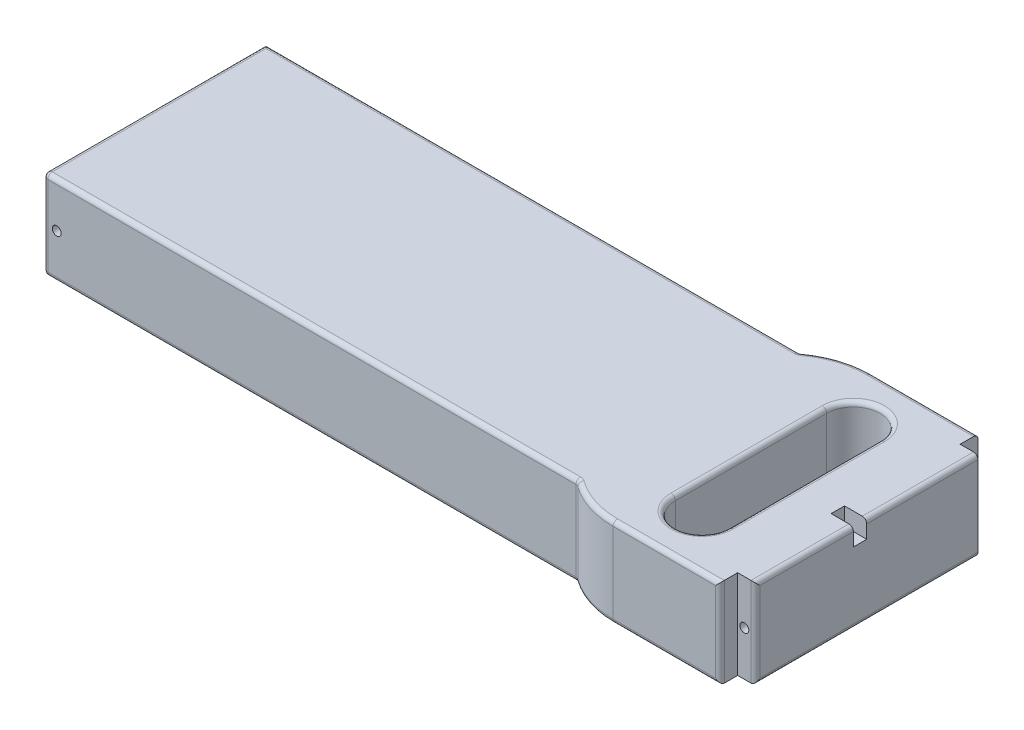
SolidWorks part; units mm, degrees
ref_plane "Alzado" through (0, 0, 0) normal (0, 0, 1) x (1, 0, 0)
ref_plane "Planta" through (0, 0, 0) normal (0, 1, 0) x (1, 0, 0)
ref_plane "Vista lateral" through (0, 0, 0) normal (1, 0, 0) x (0, 0, -1)
sketch "Croquis1" plane through (0, 0, 0) normal (0, 1, 0) x (1, 0, 0)
  line L0 (0, 0) -> (0, 1.3281)
  line L2 (8, 1.3281) -> (8, -1.1719)
  line L4 (0, -1.1719) -> (0, 0)
  line L5 (6, 1.3281) -> (0, 1.3281)
  line L10 (0, -1.1719) -> (6, -1.1719)
  line L11 (7.8, -1.3719) -> (7.8, -1.1719)
  line L12 (7.8, -1.1719) -> (8, -1.1719)
  line L13 (6.6, -1.3719) -> (7.8, -1.3719)
  line L14 (7.8, 1.5281) -> (7.8, 1.3281)
  line L15 (7.8, 1.3281) -> (8, 1.3281)
  line L16 (6.6, 1.5281) -> (7.8, 1.5281)
  arc A0 (6, 1.3281) -> (6.6, 1.5281) centre (6.6, 0.5281) cw
  arc A1 (6, -1.1719) -> (6.6, -1.3719) centre (6.6, -0.3719) ccw
  point P3 (6, 1.3281)
  point P11 (6, -1.1719)
  dimension "D6" = 1
  dimension "D10" = 1
  dimension "D1" = 2.5
  dimension "D2" = 8
  dimension "D3" = 1.1719
  dimension "D4" = 2
  dimension "D5" = 0.2
  dimension "D7" = 2.5
  dimension "D8" = 0.2
  dimension "D9" = 1.2
  dimension "D11" = 6
  dimension "D13" = 0.2
extrude "Saliente-Extruir1" add sketch "Croquis1" along normal blind 1
fillet "Redondeo1" radius 0.05 21 edges at (8, 0, -0.0781) (6.2838, 0, -1.4768) (3, 0, -1.3281) (0, 0, -0.0781) (6.2838, 0, 1.3206) (0, 0.5, 1.1719) (6, 0.5, 1.1719) (3, 0, 1.1719) (3, 1, -1.3281) (6.2838, 1, -1.4768) (8, 1, -0.0781) (6.2838, 1, 1.3206) (3, 1, 1.1719) (0, 1, -0.0781) (7.2, 0, 1.3719) (7.2, 0, -1.5281) (7.2, 1, -1.5281) (7.2, 1, 1.3719) (7.8, 0.5, 1.3719) (8, 0.5, 1.1719) (6, 0.5, -1.3281)
sketch "Croquis2" plane through (0, 1, 0) normal (0, 1, 0) x (1, 0, 0)
  line L5 (7.3, -0.7719) -> (7.3, 0.9281)
  line L7 (6.7, -0.7719) -> (6.7, 0.9281)
  line L8 (7.3, -0.7719) -> (6.7, 0.9281) construction
  line L9 (7.3, 0.9281) -> (6.7, -0.7719) construction
  line L12 (6.6, -1.3219) -> (7.8, -1.3219) construction
  arc A2 (6.7, 0.9281) -> (7.3, 0.9281) centre (7, 0.9281) cw
  arc A3 (6.7, -0.7719) -> (7.3, -0.7719) centre (7, -0.7719) ccw
  point P0 (7, 0.0781)
  dimension "D1" = 0.3
  dimension "D2" = 1.7
  dimension "D4" = 0.55
  dimension "D3" = 7
extrude "Cortar-Extruir1" cut sketch "Croquis2" against normal blind 1
fillet "Redondeo2" radius 0.05 8 edges at (7.3, 0, -0.0781) (7, 0, 1.0719) (6.7, 0, -0.0781) (7.3, 1, -0.0781) (7, 1, 1.0719) (6.7, 1, -0.0781) (7, 0, -1.2281) (7, 1, -1.2281)
sketch "Croquis3" plane through (0, 0, 1.1719) normal (0, 0, 1) x (1, 0, 0)
  line L0 (7.8, 1) -> (7.95, 1) construction
  line L2 (7.95, 0) -> (7.95, 1) construction
  line L4 (0, 0.05) -> (0, 0.95) construction
  line L5 (0.05, 1) -> (5.9836, 1) construction
  circle A0 centre (7.875, 0.5005) radius 0.05
  circle A1 centre (0.15, 0.5005) radius 0.05
  dimension "D1" = 0.4995
  dimension "D2" = 0.075
  dimension "D3" = 0.1
  dimension "D4" = 0.1
  dimension "D5" = 0.15
  dimension "D6" = 0.4995
extrude "Cortar-Extruir2" cut sketch "Croquis3" against normal through all
sketch "Croquis4" plane through (0, 1, 0) normal (0, 1, 0) x (1, 0, 0)
  line L1 (7.95, -1.1719) -> (7.95, 1.3281) construction
  line L2 (7.95, -0.0719) -> (7.75, -0.0719)
  line L3 (7.75, -0.0719) -> (7.75, 0.0781)
  line L4 (7.75, 0.0781) -> (7.95, 0.0781)
  line L6 (7.95, -0.0719) -> (8.1819, -0.0719)
  line L7 (8.1819, 0.0781) -> (7.95, 0.0781)
  line L8 (8.1819, 0.0781) -> (8.1819, -0.0719)
  dimension "D1" = 0.15
  dimension "D2" = 0.2
extrude "Cortar-Extruir3" cut sketch "Croquis4" against normal blind 0.2
